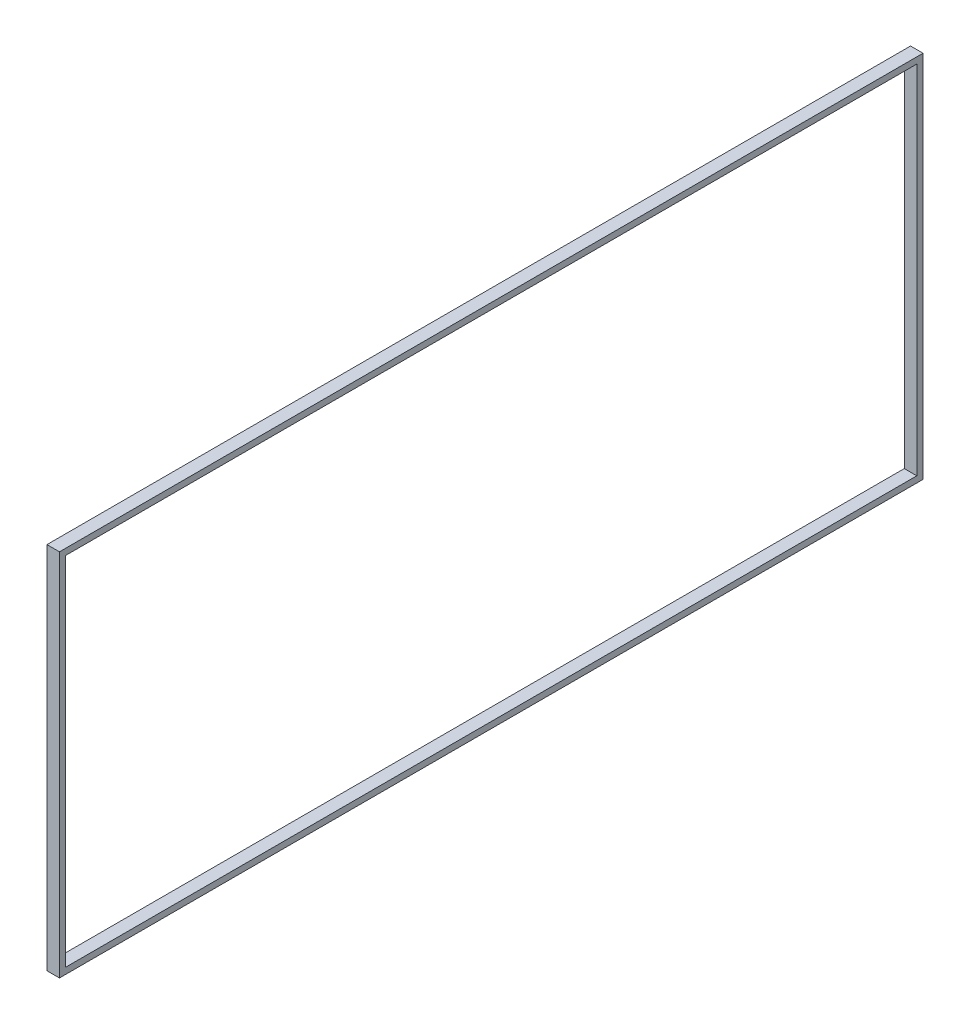
SolidWorks part; units mm, degrees
ref_plane "Front Plane" through (0, 0, 0) normal (0, 0, 1) x (1, 0, 0)
ref_plane "Top Plane" through (0, 0, 0) normal (0, 1, 0) x (1, 0, 0)
ref_plane "Right Plane" through (0, 0, 0) normal (1, 0, 0) x (0, 0, -1)
other "STL Graphics1"
ref_plane "Plane1" through (1477.78, 0, 0) normal (1, 0, 0) x (0, 0, -1)
sketch "Sketch1" plane through (1477.78, 0, 0) normal (1, 0, 0) x (0, 0, -1)
  line L1 (-3585.202, 1978.7195) -> (3320.2, 1978.7195)
  line L2 (-3585.202, 1978.7195) -> (-3585.202, -972.6531)
  line L3 (-3585.202, -972.6531) -> (3320.2, -972.6531)
  line L4 (3320.2, 1978.7195) -> (3320.2, -972.6531)
  line L5 (-3535.202, 1928.7195) -> (3270.2, 1928.7195)
  line L6 (-3535.202, 1928.7195) -> (-3535.202, -922.6531)
  line L7 (-3535.202, -922.6531) -> (3270.2, -922.6531)
  line L8 (3270.2, 1928.7195) -> (3270.2, -922.6531)
  dimension "D1" = 50
  dimension "D2" = 50
  dimension "D3" = 50
  dimension "D4" = 50
  dimension "D5" = 3535.202
  dimension "D6" = 1928.7195
  dimension "D7" = 3270.2
extrude "Boss-Extrude1" add sketch "Sketch1" against normal blind 100
